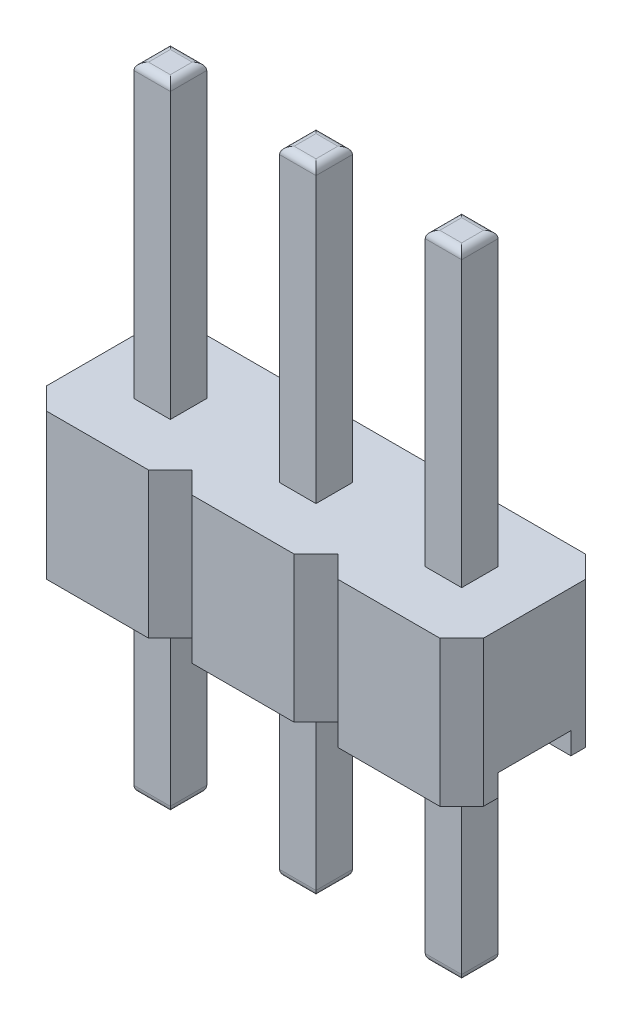
SolidWorks part; units mm, degrees
ref_plane "Płaszczyzna przednia" through (0, 0, 0) normal (0, 0, 1) x (1, 0, 0)
ref_plane "Płaszczyzna górna" through (0, 0, 0) normal (0, 1, 0) x (1, 0, 0)
ref_plane "Płaszczyzna prawa" through (0, 0, 0) normal (1, 0, 0) x (0, 0, -1)
sketch "Szkic1" plane through (0, 0, 0) normal (0, 1, 0) x (1, 0, 0)
  line L1 (-3, 1) -> (3, 1)
  line L2 (-3, 1) -> (-3, -1)
  line L3 (-3, -1) -> (3, -1)
  line L4 (3, 1) -> (3, -1)
  line L5 (-3, 1) -> (3, -1) construction
  line L6 (-3, -1) -> (3, 1) construction
  point P0 (0, 0)
  dimension "D1" = 6
  dimension "D2" = 2
extrude "Dodanie-wyciągnięcie1" add sketch "Szkic1" along normal blind 2
sketch "Szkic2" plane through (0, 2, 0) normal (0, 1, 0) x (1, 0, 0)
  line L0 (2.7, 1) -> (3, 0.7)
  line L1 (3, 1) -> (-3, 1) construction
  line L2 (3, -1) -> (3, 1) construction
  line L3 (3, 0.7) -> (3, -0.7)
  line L4 (3, -0.7) -> (2.7, -1)
  line L5 (-3, -1) -> (3, -1) construction
  line L6 (2.7, -1) -> (1.3, -1)
  line L7 (1.3, -1) -> (1, -0.7)
  line L8 (1, -0.7) -> (0.7, -1)
  line L9 (0.7, -1) -> (-0.7, -1)
  line L10 (-0.7, -1) -> (-1, -0.7)
  line L11 (-1, -0.7) -> (-1.3, -1)
  line L12 (-1.3, -1) -> (-2.7, -1)
  line L13 (-2.7, -1) -> (-3, -0.7)
  line L14 (-3, 1) -> (-3, -1) construction
  line L15 (-3, -0.7) -> (-3, 0.7)
  line L16 (-3, 0.7) -> (-2.7, 1)
  line L17 (-2.7, 1) -> (-1.3, 1)
  line L18 (-1.3, 1) -> (-1, 0.7)
  line L19 (-1, 0.7) -> (-0.7, 1)
  line L20 (-0.7, 1) -> (0.7, 1)
  line L23 (1.3, 1) -> (2.7, 1)
  line L24 (0.7, 1) -> (1, 0.7)
  line L25 (1.3, 1) -> (1, 0.7)
  line L27 (4, 2) -> (-4, 2)
  line L28 (4, 2) -> (4, -2)
  line L29 (4, -2) -> (-4, -2)
  line L30 (-4, 2) -> (-4, -2)
  dimension "D1" = 0.3
  dimension "D2" = 0.3
  dimension "D3" = 0.3
  dimension "D4" = 0.3
  dimension "D5" = 1.7
  dimension "D6" = 2.3
  dimension "D7" = 2.3
  dimension "D8" = 1.7
  dimension "D9" = 0.3
  dimension "D10" = 0.3
  dimension "D11" = 0.3
  dimension "D12" = 1.7
  dimension "D13" = 2.3
  dimension "D14" = 2.3
  dimension "D15" = 1.7
  dimension "D16" = 1
  dimension "D17" = 1
  dimension "D18" = 1
  dimension "D19" = 1
extrude "Wytnij-wyciągnięcie1" cut sketch "Szkic2" against normal blind 2
sketch "Szkic4" plane through (-3, 0, 0) normal (-1, 0, 0) x (0, 0, 1)
  line L0 (-0.7, 0) -> (0.7, 0) construction
  line L1 (-0.5, 0) -> (0.5, 0)
  line L2 (-0.5, 0) -> (-0.5, 0.3)
  line L3 (-0.5, 0.3) -> (0.5, 0.3)
  line L4 (0.5, 0) -> (0.5, 0.3)
  line L5 (-0.7, 0) -> (-0.7, 2) construction
  line L6 (0.7, 0) -> (0.7, 2) construction
  dimension "D1" = 0.2
  dimension "D2" = 0.2
  dimension "D3" = 0.3
extrude "Wytnij-wyciągnięcie2" cut sketch "Szkic4" against normal up to next
sketch "Szkic3" plane through (0, 0, 0) normal (0, 1, 0) x (1, 0, 0)
  line L1 (0.25, 0.25) -> (-0.25, 0.25)
  line L2 (0.25, 0.25) -> (0.25, -0.25)
  line L3 (0.25, -0.25) -> (-0.25, -0.25)
  line L4 (-0.25, 0.25) -> (-0.25, -0.25)
  line L5 (0.25, 0.25) -> (-0.25, -0.25) construction
  line L6 (0.25, -0.25) -> (-0.25, 0.25) construction
  line L7 (2.25, 0.25) -> (1.75, 0.25)
  line L8 (2.25, 0.25) -> (2.25, -0.25)
  line L9 (2.25, -0.25) -> (1.75, -0.25)
  line L10 (1.75, 0.25) -> (1.75, -0.25)
  line L11 (2.25, 0.25) -> (1.75, -0.25) construction
  line L12 (2.25, -0.25) -> (1.75, 0.25) construction
  line L13 (-1.75, 0.25) -> (-2.25, 0.25)
  line L14 (-1.75, 0.25) -> (-1.75, -0.25)
  line L15 (-1.75, -0.25) -> (-2.25, -0.25)
  line L16 (-2.25, 0.25) -> (-2.25, -0.25)
  line L17 (-1.75, 0.25) -> (-2.25, -0.25) construction
  line L18 (-1.75, -0.25) -> (-2.25, 0.25) construction
  point P0 (0, 0)
  point P6 (2, 0)
  point P11 (-2, 0)
  dimension "D1" = 0.5
  dimension "D2" = 0.5
  dimension "D3" = 2
  dimension "D4" = 2
  dimension "D5" = 0.5
  dimension "D6" = 0.5
extrude "Dodanie-wyciągnięcie2" add sketch "Szkic3" along normal blind 6 and the other way blind 2.7
fillet "Zaokrąglenie1" radius 0.1 24 edges at (-2, 6, -0.25) (-1.75, 6, 0) (-2, 6, 0.25) (-2.25, 6, 0) (0, 6, -0.25) (0.25, 6, 0) (0, 6, 0.25) (-0.25, 6, 0) (2, 6, -0.25) (2.25, 6, 0) (2, 6, 0.25) (1.75, 6, 0) (2, -2.7, 0.25) (2.25, -2.7, 0) (2, -2.7, -0.25) (1.75, -2.7, 0) (0, -2.7, 0.25) (0.25, -2.7, 0) (0, -2.7, -0.25) (-0.25, -2.7, 0) (-2, -2.7, 0.25) (-1.75, -2.7, 0) (-2, -2.7, -0.25) (-2.25, -2.7, 0)
